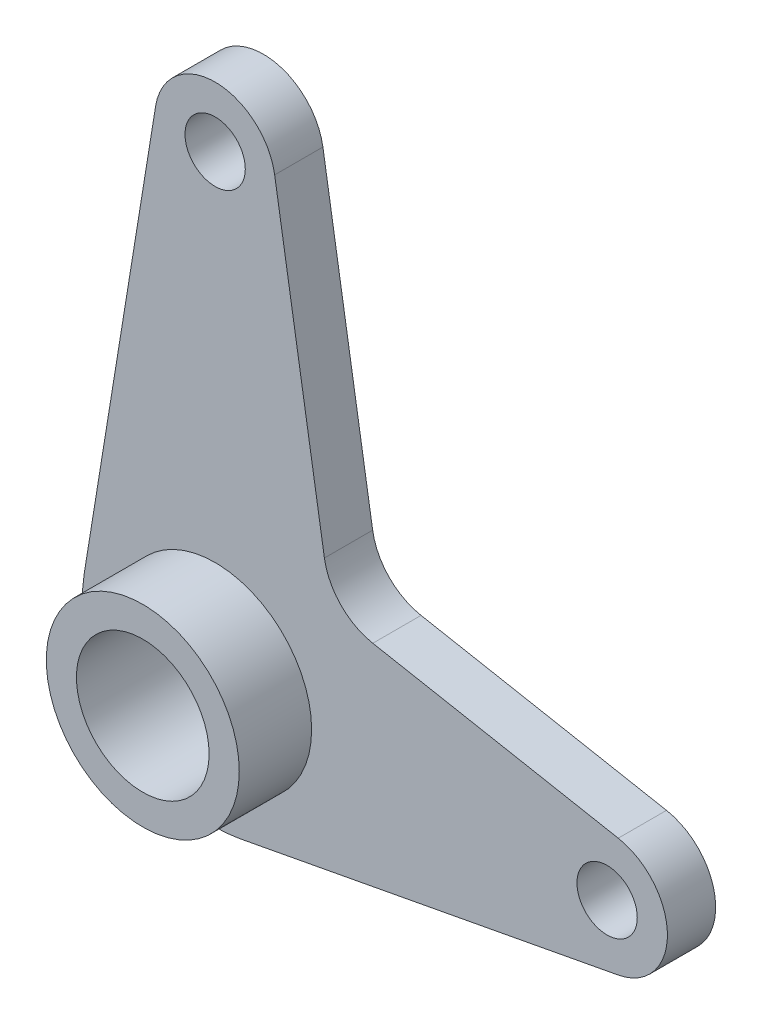
SolidWorks part; units mm, degrees
ref_plane "Front Plane" through (0, 0, 0) normal (0, 0, 1) x (1, 0, 0)
ref_plane "Top Plane" through (0, 0, 0) normal (0, 1, 0) x (1, 0, 0)
ref_plane "Right Plane" through (0, 0, 0) normal (1, 0, 0) x (0, 0, -1)
sketch "Sketch1" plane through (0, 0, 0) normal (0, 0, 1) x (1, 0, 0)
  line L0 (0, 0) -> (0, 75) construction
  line L1 (0, 0) -> (65, 0) construction
  line L2 (-9.8712, 76.6) -> (-21.7166, 3.52)
  line L3 (4.0615, -21.6218) -> (66.8462, -9.8281)
  line L4 (9.8712, 76.6) -> (18.1211, 25.7024)
  line L6 (26.1459, 17.4744) -> (66.8464, 9.8281)
  arc A0 (-21.7166, 3.52) -> (4.0615, -21.6218) centre (0, 0) ccw
  arc A1 (9.8712, 76.6) -> (-9.8712, 76.6) centre (0, 75) ccw
  arc A2 (66.8462, -9.8281) -> (66.8464, 9.8281) centre (65, 0) ccw
  circle A3 centre (0, 75) radius 5
  circle A4 centre (65, 0) radius 5
  arc A5 (18.1211, 25.7024) -> (26.1459, 17.4744) centre (27.9922, 27.3024) ccw
  dimension "D1" = 44
  dimension "D2" = 20
  dimension "D3" = 20
  dimension "D4" = 10
  dimension "D5" = 10
  dimension "D8" = 20
  dimension "D9" = 10.64
  dimension "D6" = 75
  dimension "D7" = 65
extrude "Boss-Extrude1" add sketch "Sketch1" along normal blind 8
sketch "Sketch4" plane through (0, 0, 8) normal (0, 0, 1) x (1, 0, 0)
  circle A0 centre (0, 0) radius 16
  dimension "D1" = 32
extrude "Boss-Extrude3" add sketch "Sketch4" along normal blind 12
sketch "Sketch5" plane through (0, 0, 20) normal (0, 0, 1) x (1, 0, 0)
  circle A0 centre (0, 0) radius 11
  dimension "D1" = 22
extrude "Cut-Extrude3" cut sketch "Sketch5" against normal through all
